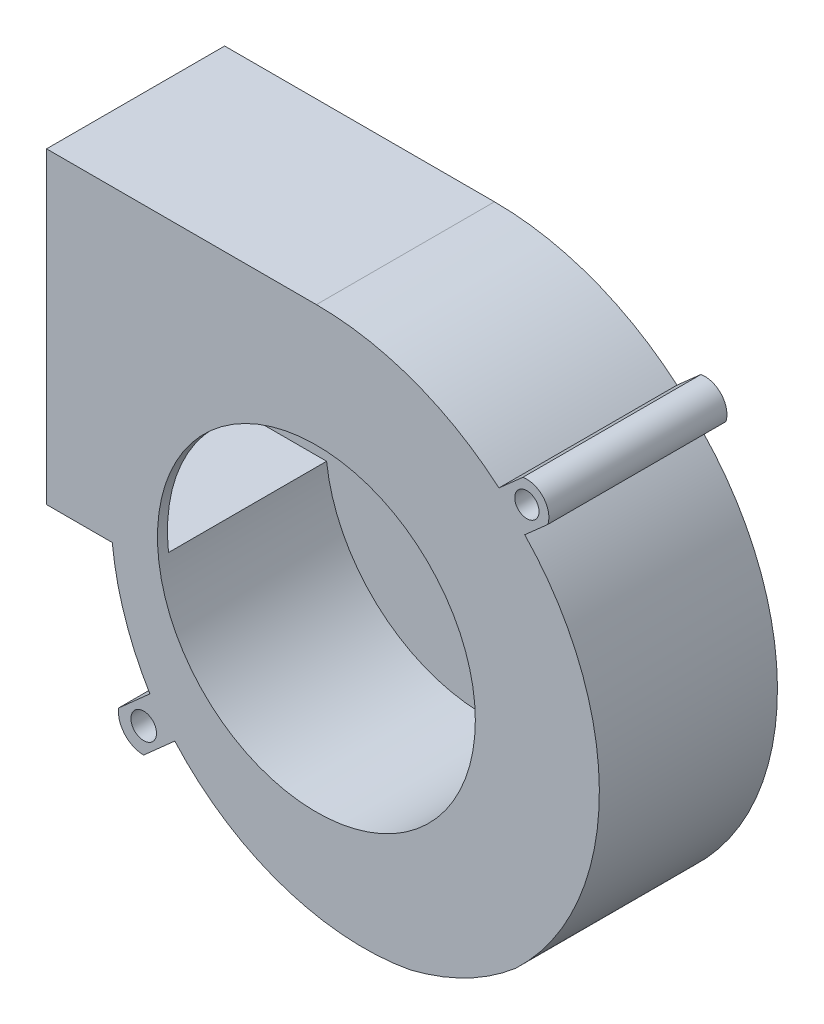
SolidWorks part; units mm, degrees
ref_plane "Front Plane" through (0, 0, 0) normal (0, 0, 1) x (1, 0, 0)
ref_plane "Top Plane" through (0, 0, 0) normal (0, 1, 0) x (1, 0, 0)
ref_plane "Right Plane" through (0, 0, 0) normal (1, 0, 0) x (0, 0, -1)
sketch "Sketch1" plane through (0, 0, 0) normal (0, 0, 1) x (1, 0, 0)
  line L0 (-67.4905, -8.9257) -> (-67.4905, -66.0182)
  line L1 (-67.4905, -66.0182) -> (-55.3154, -66.0182)
  line L2 (-67.4905, -8.9257) -> (-17.4905, -8.9257)
  line L3 (-89.9001, -60.9257) -> (51.7267, -60.9257) construction
  line L4 (-17.4905, 44.503) -> (-17.4905, -114.3486) construction
  line L5 (21.5095, -88.5113) -> (21.5095, 44.503) construction
  line L6 (20.7515, -17.5217) -> (16.3362, -21.432)
  line L7 (25.3925, -22.762) -> (21.1141, -26.5511)
  line L8 (-49.4997, -97.2189) -> (-43.7325, -92.0869)
  line L9 (-54.153, -91.9895) -> (-48.3449, -86.8212)
  circle A0 centre (21.5095, -21.5257) radius 2.25
  arc A3 (20.7515, -17.5217) -> (25.3925, -22.762) centre (21.5095, -21.5257) cw
  circle A4 centre (-49.4905, -92.5257) radius 2.3721
  arc A5 (-17.4905, -8.9257) -> (16.3362, -21.432) centre (-17.4905, -60.9257) cw
  arc A6 (21.1141, -26.5511) -> (19.4151, -96.987) centre (-14.6994, -60.9257) cw
  arc A7 (19.4151, -96.987) -> (-0.1036, -106.9902) centre (-11.3887, -60.9257) cw
  arc A9 (-54.153, -91.9895) -> (-49.4997, -97.2189) centre (-49.4905, -92.5257) ccw
  arc A10 (-0.1036, -106.9902) -> (-43.7325, -92.0869) centre (-8.7282, -60.9257) cw
  arc A11 (-48.3449, -86.8212) -> (-55.3154, -66.0182) centre (-5.5893, -60.9257) cw
  point P25 (-43.8363, -92.0869)
  point P31 (0, 0)
  dimension "D6" = 4.5
  dimension "D10" = 3.5
  dimension "D1" = 50
  dimension "D2" = 52
  dimension "D3" = 39
  dimension "D4" = 39.4
  dimension "D5" = 3.5
  dimension "D7" = 3.5
  dimension "D8" = 32
  dimension "D9" = 31.6
  dimension "D11" = 3.5
  dimension "D12" = 98.0645
extrude "Boss-Extrude1" add sketch "Sketch1" along normal blind 33
sketch "Sketch2" plane through (0, 0, 33) normal (0, 0, 1) x (1, 0, 0)
  line L0 (-17.4905, -8.9257) -> (-17.4905, -113.694) construction
  line L1 (-83.1712, -60.9257) -> (48.5467, -60.9257) construction
  line L3 (-17.4905, -8.9257) -> (-67.4905, -8.9257) construction
  arc A0 (16.3362, -21.432) -> (-17.4905, -8.9257) centre (-17.4905, -60.9257) ccw construction
  circle A1 centre (-17.4905, -60.9257) radius 29.45
  dimension "D2" = 58.9
  dimension "D1" = 52
extrude "Cut-Extrude1" cut sketch "Sketch2" against normal blind 31.15
sketch "Sketch3" plane through (-67.4905, 0, 0) normal (-1, 0, 0) x (0, 0, 1)
  line L0 (1.85, -10.7757) -> (31.15, -10.7757)
  line L1 (31.15, -10.7757) -> (31.15, -64.2682)
  line L2 (31.15, -64.2682) -> (1.85, -64.2682)
  line L3 (1.85, -64.2682) -> (1.85, -10.7757)
  line L4 (33, -8.9257) -> (0, -8.9257) construction
  line L5 (0, -8.9257) -> (0, -66.0182) construction
  line L6 (33, -8.9257) -> (33, -66.0182) construction
  line L7 (33, -66.0182) -> (0, -66.0182) construction
  dimension "D1" = 1.85
  dimension "D2" = 1.85
  dimension "D3" = 1.85
  dimension "D4" = 1.75
extrude "Cut-Extrude2" cut sketch "Sketch3" against normal blind 58
